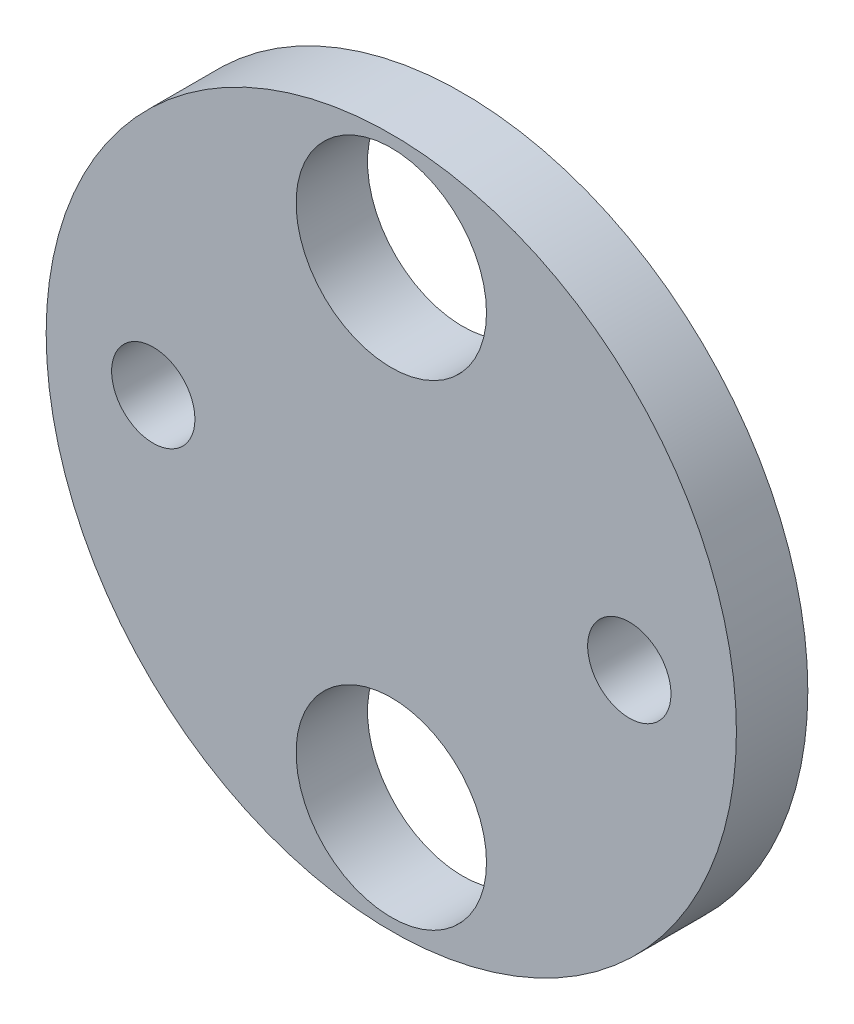
SolidWorks part; units mm, degrees
ref_plane "Front Plane" through (0, 0, 0) normal (0, 0, 1) x (1, 0, 0)
ref_plane "Top Plane" through (0, 0, 0) normal (0, 1, 0) x (1, 0, 0)
ref_plane "Right Plane" through (0, 0, 0) normal (1, 0, 0) x (0, 0, -1)
sketch "Sketch1" plane through (0, 0, 0) normal (0, 0, 1) x (1, 0, 0)
  line L0 (-10, 0) -> (10, 0) construction
  line L1 (0, -10) -> (0, 10) construction
  circle A0 centre (0, 0) radius 14.5
  circle A1 centre (-10, 0) radius 1.75
  circle A2 centre (10, 0) radius 1.75
  circle A3 centre (0, -10) radius 4
  circle A4 centre (0, 10) radius 4
  dimension "D1" = 29
  dimension "D3" = 3.5
  dimension "D4" = 8
  dimension "D2" = 20
extrude "Boss-Extrude1" add sketch "Sketch1" along normal blind 3
